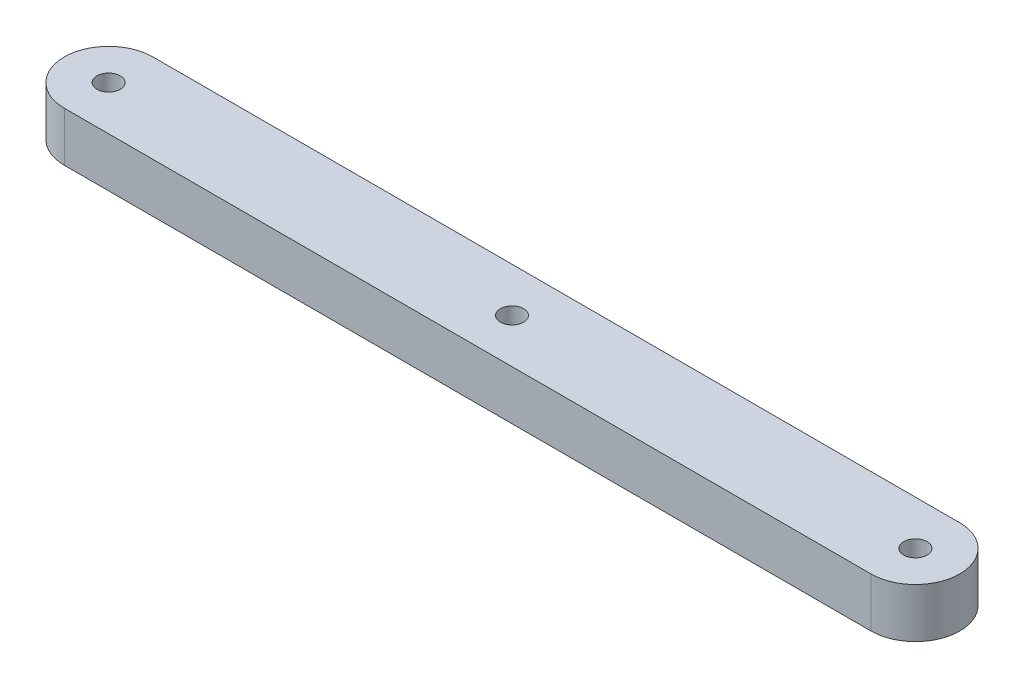
SolidWorks part; units mm, degrees
ref_plane "Front Plane" through (0, 0, 0) normal (0, 0, 1) x (1, 0, 0)
ref_plane "Top Plane" through (0, 0, 0) normal (0, 1, 0) x (1, 0, 0)
ref_plane "Right Plane" through (0, 0, 0) normal (1, 0, 0) x (0, 0, -1)
sketch "Sketch1" plane through (0, 0, 0) normal (0, 1, 0) x (1, 0, 0)
  line L0 (0, 0) -> (145.04, 0) construction
  line L1 (0, 7.9735) -> (145.04, 7.9735)
  line L2 (0, -7.9735) -> (145.04, -7.9735)
  arc A0 (0, 7.9735) -> (0, -7.9735) centre (0, 0) ccw
  arc A1 (145.04, -7.9735) -> (145.04, 7.9735) centre (145.04, 0) ccw
  circle A2 centre (145.04, 0) radius 2.1
  circle A3 centre (72.52, 0) radius 2.1
  circle A4 centre (0, 0) radius 2.1
  point P3 (72.52, 0)
  dimension "D1" = 4.2
  dimension "D2" = 4.2
  dimension "D3" = 4.2
extrude "Boss-Extrude1" add sketch "Sketch1" along normal blind 8.89
